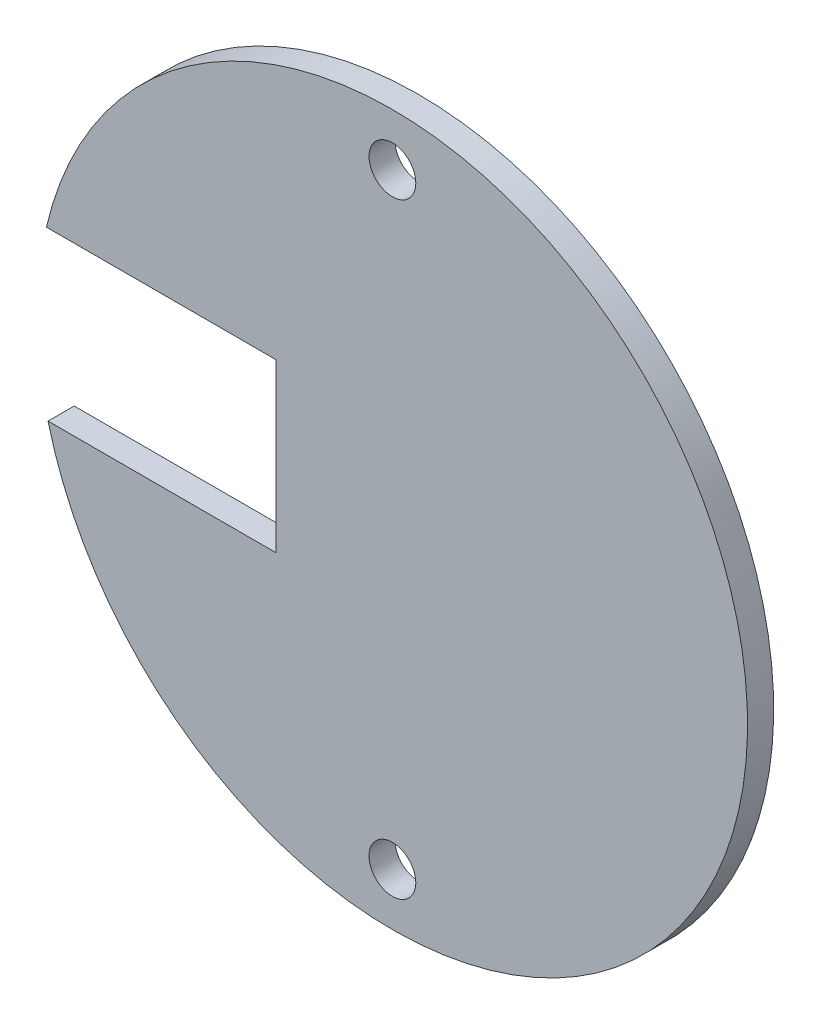
SolidWorks part; units mm, degrees
ref_plane "Front Plane" through (0, 0, 0) normal (0, 0, 1) x (1, 0, 0)
ref_plane "Top Plane" through (0, 0, 0) normal (0, 1, 0) x (1, 0, 0)
ref_plane "Right Plane" through (0, 0, 0) normal (1, 0, 0) x (0, 0, -1)
sketch "Sketch2" plane through (0, 0, 0) normal (0, 0, 1) x (1, 0, 0)
  line L0 (-21.032, 4.8768) -> (-7.085, 4.8768) construction
  line L1 (-7.085, 4.8768) -> (-7.085, -5.2832) construction
  line L2 (-7.085, -5.2832) -> (-20.9336, -5.2832) construction
  line L3 (-21.032, 4.8768) -> (-7.085, 4.8768)
  line L4 (-7.085, 4.8768) -> (-7.085, -5.2832)
  line L5 (-7.085, -5.2832) -> (-20.9336, -5.2832)
  arc A0 (-20.9336, -5.2832) -> (-21.032, 4.8768) centre (0, 0) ccw
  circle A1 centre (0, 18.415) radius 1.4224 construction
  circle A2 centre (0, -18.415) radius 1.4224 construction
  circle A3 centre (0, 18.415) radius 1.4224
  circle A4 centre (0, -18.415) radius 1.4224
extrude "Boss-Extrude1" add sketch "Sketch2" along normal blind 1.5875
